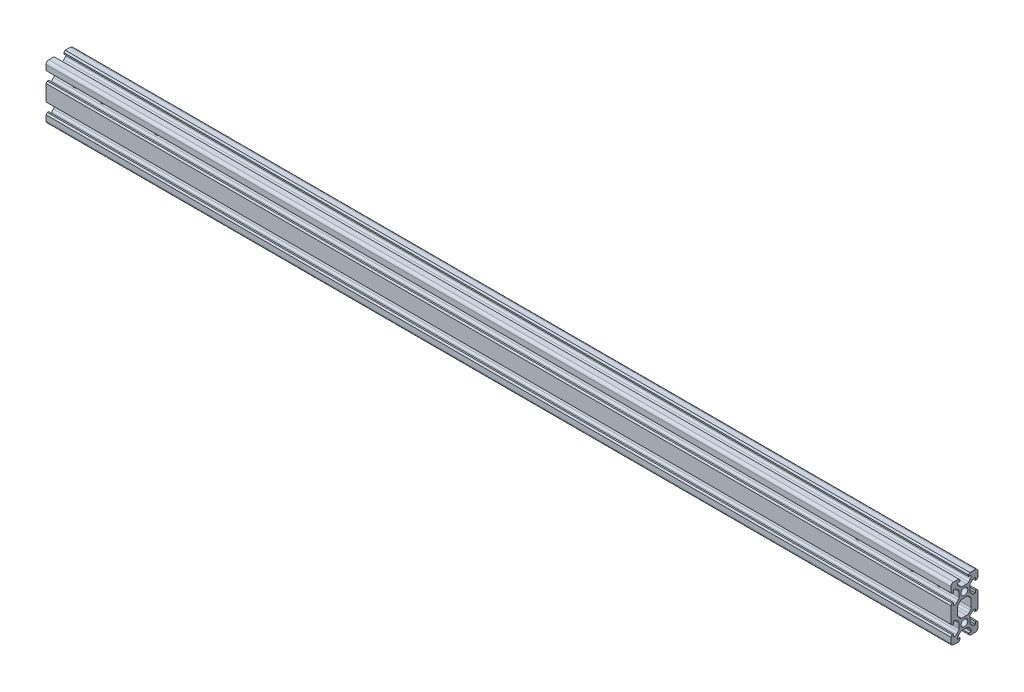
SolidWorks part; units mm, degrees
ref_plane "Front Plane" through (0, 0, 0) normal (0, 0, 1) x (1, 0, 0)
ref_plane "Top Plane" through (0, 0, 0) normal (0, 1, 0) x (1, 0, 0)
ref_plane "Right Plane" through (0, 0, 0) normal (1, 0, 0) x (0, 0, -1)
sketch "Sketch1" plane through (0, 0, 0) normal (1, 0, 0) x (0, 0, -1)
  line B0 (6.9, 38) -> (5, 38)
  line B1 (19, 6.9) -> (20, 5.9)
  line B2 (14.4142, 15.8284) -> (13.1236, 14.5379)
  line B3 (20, 14.1) -> (19, 13.1)
  line B4 (15.8284, 5.5858) -> (14.5379, 6.8764)
  line B5 (17.2426, 5) -> (18, 5)
  line B6 (18, 6.9) -> (18, 5)
  line B7 (17.2426, 15) -> (18, 15)
  line B8 (8.2906, 13.9521) -> (11.7094, 13.9521)
  line B9 (18, 15) -> (18, 13.1)
  line B10 (18, 13.1) -> (19, 13.1)
  line B11 (18, 6.9) -> (19, 6.9)
  line B12 (13.9521, 11.7094) -> (13.9521, 8.2906)
  line B13 (6.8764, 14.5379) -> (5.5858, 15.8284)
  line B14 (20, 5.9) -> (20, 2)
  line B15 (14.5379, 13.1236) -> (15.8284, 14.4142)
  line B16 (6.9, 1) -> (5.9, 0)
  line B17 (18, 0) -> (14.1, 0)
  line B18 (14.1, 0) -> (13.1, 1)
  line B19 (5.5858, 4.1716) -> (6.8764, 5.4621)
  line B20 (5, 2.7574) -> (5, 2)
  line B21 (6.9, 2) -> (5, 2)
  line B22 (15, 2.7574) -> (15, 2)
  line B23 (15, 2) -> (13.1, 2)
  line B24 (13.1, 2) -> (13.1, 1)
  line B25 (6.9, 2) -> (6.9, 1)
  line B26 (11.7094, 6.0479) -> (8.2906, 6.0479)
  line B27 (5.9, 0) -> (2, 0)
  line B28 (13.1236, 5.4621) -> (14.4142, 4.1716)
  line B29 (1, 13.1) -> (0, 14.1)
  line B30 (0, 2) -> (0, 5.9)
  line B31 (0, 5.9) -> (1, 6.9)
  line B32 (4.1716, 14.4142) -> (5.4621, 13.1236)
  line B33 (2.7574, 15) -> (2, 15)
  line B34 (2, 13.1) -> (2, 15)
  line B35 (2.7574, 5) -> (2, 5)
  line B36 (2, 5) -> (2, 6.9)
  line B37 (2, 6.9) -> (1, 6.9)
  line B38 (2, 13.1) -> (1, 13.1)
  line B39 (6.0479, 8.2906) -> (6.0479, 11.7094)
  line B40 (5.4621, 6.8764) -> (4.1716, 5.5858)
  line B41 (19, 26.9) -> (20, 25.9)
  line B42 (15, 38) -> (13.1, 38)
  line B43 (14.1, 40) -> (13.1, 39)
  line B44 (14.4142, 35.8284) -> (13.1236, 34.5379)
  line B45 (18, 35) -> (18, 33.1)
  line B46 (6.9, 38) -> (6.9, 39)
  line B47 (18, 40) -> (14.1, 40)
  line B48 (5.9, 40) -> (2, 40)
  line B49 (0, 25.9) -> (1, 26.9)
  line B50 (17.2426, 25) -> (18, 25)
  line B51 (5, 37.2426) -> (5, 38)
  line B52 (18, 26.9) -> (19, 26.9)
  line B53 (13.1, 38) -> (13.1, 39)
  line B54 (2, 26.9) -> (1, 26.9)
  line B55 (20, 34.1) -> (19, 33.1)
  line B56 (5, 22.7574) -> (5, 17.2426)
  line B57 (20, 34.1) -> (20, 38)
  line B58 (0, 38) -> (0, 34.1)
  line B59 (13.1236, 25.4621) -> (14.4142, 24.1716)
  line B60 (2, 25) -> (2, 26.9)
  line B61 (6.0479, 28.2906) -> (6.0479, 31.7094)
  line B62 (18, 33.1) -> (19, 33.1)
  line B63 (15, 37.2426) -> (15, 38)
  line B64 (2, 33.1) -> (2, 35)
  line B65 (18, 26.9) -> (18, 25)
  line B66 (11.7094, 26.0479) -> (8.2906, 26.0479)
  line B67 (17.2426, 35) -> (18, 35)
  line B68 (20, 25.9) -> (20, 14.1)
  line B69 (1, 33.1) -> (0, 34.1)
  line B70 (14.5379, 33.1236) -> (15.8284, 34.4142)
  line B71 (4.1716, 34.4142) -> (5.4621, 33.1236)
  line B72 (13.9521, 31.7094) -> (13.9521, 28.2906)
  line B73 (2.7574, 35) -> (2, 35)
  line B74 (8.2906, 33.9521) -> (11.7094, 33.9521)
  line B75 (6.9, 39) -> (5.9, 40)
  line B76 (5.4621, 26.8764) -> (4.1716, 25.5858)
  line B77 (0, 14.1) -> (0, 25.9)
  line B78 (5.5858, 24.1716) -> (6.8764, 25.4621)
  line B79 (15.8284, 25.5858) -> (14.5379, 26.8764)
  line B80 (6.8764, 34.5379) -> (5.5858, 35.8284)
  line B81 (15, 22.7574) -> (15, 17.2426)
  line B82 (2.7574, 25) -> (2, 25)
  line B83 (2, 33.1) -> (1, 33.1)
  circle B84 centre (10, 10) radius 2.5
  arc B85 (5.4621, 13.1236) -> (6.0479, 11.7094) centre (4.0479, 11.7094) cw
  arc B86 (4.1716, 14.4142) -> (2.7574, 15) centre (2.7574, 13) ccw
  arc B87 (5, 17.2426) -> (5.5858, 15.8284) centre (7, 17.2426) ccw
  arc B88 (15, 17.2426) -> (14.4142, 15.8284) centre (13, 17.2426) cw
  arc B89 (17.2426, 15) -> (15.8284, 14.4142) centre (17.2426, 13) ccw
  arc B90 (15.8284, 5.5858) -> (17.2426, 5) centre (17.2426, 7) ccw
  arc B91 (15, 2.7574) -> (14.4142, 4.1716) centre (13, 2.7574) ccw
  arc B92 (5.5858, 4.1716) -> (5, 2.7574) centre (7, 2.7574) ccw
  arc B93 (2.7574, 5) -> (4.1716, 5.5858) centre (2.7574, 7) ccw
  arc B94 (6.0479, 8.2906) -> (5.4621, 6.8764) centre (4.0479, 8.2906) cw
  arc B95 (6.8764, 5.4621) -> (8.2906, 6.0479) centre (8.2906, 4.0479) cw
  arc B96 (11.7094, 6.0479) -> (13.1236, 5.4621) centre (11.7094, 4.0479) cw
  arc B97 (14.5379, 6.8764) -> (13.9521, 8.2906) centre (15.9521, 8.2906) cw
  arc B98 (13.9521, 11.7094) -> (14.5379, 13.1236) centre (15.9521, 11.7094) cw
  arc B99 (11.7094, 13.9521) -> (13.1236, 14.5379) centre (11.7094, 15.9521) ccw
  arc B100 (8.2906, 13.9521) -> (6.8764, 14.5379) centre (8.2906, 15.9521) cw
  arc B101 (2, 0) -> (0, 2) centre (2, 2) cw
  arc B102 (20, 2) -> (18, 0) centre (18, 2) cw
  arc B103 (11.7094, 26.0479) -> (13.1236, 25.4621) centre (11.7094, 24.0479) cw
  arc B104 (13.9521, 31.7094) -> (14.5379, 33.1236) centre (15.9521, 31.7094) cw
  arc B105 (14.5379, 26.8764) -> (13.9521, 28.2906) centre (15.9521, 28.2906) cw
  arc B106 (5.5858, 24.1716) -> (5, 22.7574) centre (7, 22.7574) ccw
  arc B107 (5, 37.2426) -> (5.5858, 35.8284) centre (7, 37.2426) ccw
  arc B108 (11.7094, 33.9521) -> (13.1236, 34.5379) centre (11.7094, 35.9521) ccw
  arc B109 (15, 22.7574) -> (14.4142, 24.1716) centre (13, 22.7574) ccw
  arc B110 (2.7574, 25) -> (4.1716, 25.5858) centre (2.7574, 27) ccw
  arc B111 (15, 37.2426) -> (14.4142, 35.8284) centre (13, 37.2426) cw
  circle B112 centre (10, 30) radius 2.5
  arc B113 (8.2906, 33.9521) -> (6.8764, 34.5379) centre (8.2906, 35.9521) cw
  arc B114 (6.0479, 28.2906) -> (5.4621, 26.8764) centre (4.0479, 28.2906) cw
  arc B115 (6.8764, 25.4621) -> (8.2906, 26.0479) centre (8.2906, 24.0479) cw
  arc B116 (4.1716, 34.4142) -> (2.7574, 35) centre (2.7574, 33) ccw
  arc B117 (15.8284, 25.5858) -> (17.2426, 25) centre (17.2426, 27) ccw
  arc B118 (5.4621, 33.1236) -> (6.0479, 31.7094) centre (4.0479, 31.7094) cw
  arc B119 (2, 40) -> (0, 38) centre (2, 38) ccw
  arc B120 (17.2426, 35) -> (15.8284, 34.4142) centre (17.2426, 33) ccw
  arc B121 (20, 38) -> (18, 40) centre (18, 38) ccw
sketch_block_instance "2040-1"
sketch_block "2040" parameters "D1"=2, "D2"=2
extrude "Boss-Extrude1" add sketch "Sketch1" along normal blind 666
sketch "Sketch2" plane through (0, 0, 0) normal (0, 0, 1) x (1, 0, 0)
  line L0 (0, 30) -> (15, 30) construction
  line L1 (0, 31.7094) -> (0, 28.2906) construction
  line L2 (15, 30) -> (35, 30) construction
  line L3 (35, 30) -> (75, 30) construction
  line L4 (333, 25.9) -> (333, -23.2109) construction
  line L5 (666, 25.9) -> (0, 25.9) construction
  line L6 (631, 30) -> (591, 30) construction
  line L7 (651, 30) -> (631, 30) construction
  line L8 (666, 30) -> (651, 30) construction
  circle A0 centre (15, 30) radius 2.4
  circle A1 centre (35, 30) radius 2.4
  circle A2 centre (75, 30) radius 2.4
  circle A3 centre (591, 30) radius 2.4
  circle A4 centre (631, 30) radius 2.4
  circle A5 centre (651, 30) radius 2.4
extrude "Cut-Extrude1" cut sketch "Sketch2" against normal through all
